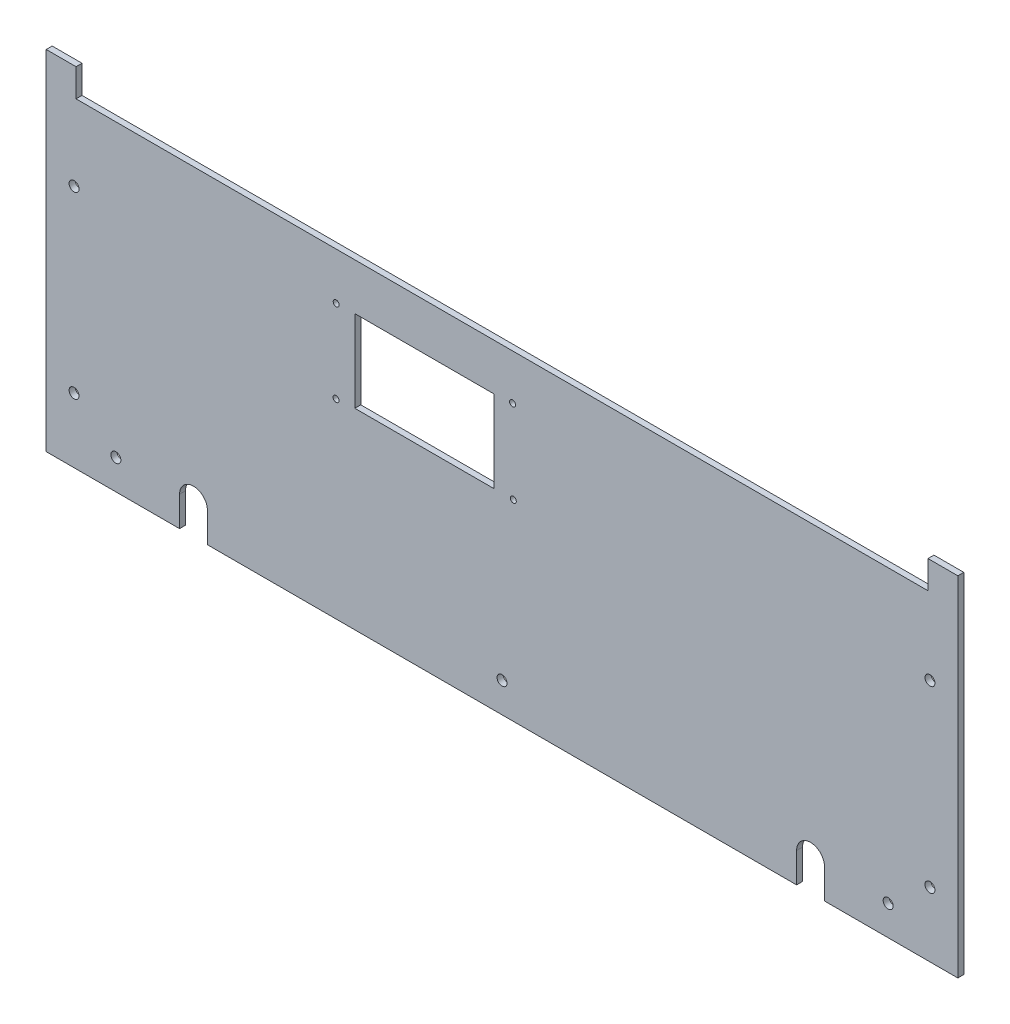
SolidWorks part; units mm, degrees
material "1345 Alloy"
ref_plane "Front Plane" through (0, 0, 0) normal (0, 0, 1) x (1, 0, 0)
ref_plane "Top Plane" through (0, 0, 0) normal (0, 1, 0) x (1, 0, 0)
ref_plane "Right Plane" through (0, 0, 0) normal (1, 0, 0) x (0, 0, -1)
sketch "Sketch1" plane through (0, 0, 0) normal (0, 0, 1) x (1, 0, 0)
  line L1 (-229, 122.5) -> (229, 122.5)
  line L2 (-229, 122.5) -> (-229, -122.5)
  line L3 (-229, -122.5) -> (229, -122.5)
  line L4 (229, 122.5) -> (229, -122.5)
  line L5 (-229, 122.5) -> (229, -122.5) construction
  line L6 (-229, -122.5) -> (229, 122.5) construction
  point P0 (0, 0)
  dimension "D1" = 458
  dimension "D2" = 245
extrude "Boss-Extrude1" add sketch "Sketch1" along normal blind 3
sketch "Sketch2" plane through (0, 0, 3) normal (0, 0, 1) x (1, 0, 0)
  line L0 (-229, -122.5) -> (-155, -122.5) construction
  line L2 (-155, -122.5) -> (-155, -107.5) construction
  line L3 (-155, -107.5) -> (-155, -122.5) construction
  line L6 (-148, -107.5) -> (-148, -122.5)
  line L11 (-162, -107.5) -> (-162, -122.5)
  line L12 (155, -122.5) -> (229, -122.5) construction
  line L13 (155, -107.5) -> (155, -122.5) construction
  line L14 (162, -107.5) -> (162, -122.5)
  line L15 (148, -107.5) -> (148, -122.5)
  line L16 (-155, -107.5) -> (155, -107.5) construction
  arc A4 (-148, -107.5) -> (-162, -107.5) centre (-155, -107.5) ccw
  arc A5 (-162, -122.5) -> (-148, -122.5) centre (-155, -122.5) ccw
  arc A6 (162, -107.5) -> (148, -107.5) centre (155, -107.5) ccw
  arc A7 (148, -122.5) -> (162, -122.5) centre (155, -122.5) ccw
  point P4 (-155, -115)
  point P13 (155, -115)
  dimension "D3" = 7
  dimension "D5" = 7
  dimension "D1" = 74
  dimension "D2" = 15
  dimension "D4" = 15
  dimension "D6" = 74
extrude "Cut-Extrude1" cut sketch "Sketch2" against normal through all
sketch "Sketch3" plane through (0, 0, 3) normal (0, 0, 1) x (1, 0, 0)
  line L19 (194, 112.5) -> (194, -107.5) construction
  line L20 (-215, 0) -> (-215, 90) construction
  line L21 (-215, 0) -> (-215, -90) construction
  line L25 (229, 0) -> (215, 0) construction
  line L26 (0, 112.5) -> (-194, 112.5) construction
  line L27 (-194, 112.5) -> (-194, -107.5) construction
  line L31 (215, 0) -> (215, 90) construction
  line L32 (215, 0) -> (215, -90) construction
  line L33 (0, 112.5) -> (194, 112.5) construction
  line L34 (0, 0) -> (0, 112.5) construction
  line L35 (0, 0) -> (0, -107.5) construction
  line L36 (-194, -107.5) -> (0, -107.5) construction
  line L37 (0, -107.5) -> (194, -107.5) construction
  line L38 (-194, 112.5) -> (-229, 112.5) construction
  line L39 (-229, 112.5) -> (-229, 122.5) construction
  circle A12 centre (-194, 112.5) radius 2.5
  circle A13 centre (-194, -107.5) radius 2.5
  circle A14 centre (194, -107.5) radius 2.5
  circle A15 centre (194, 112.5) radius 2.5
  circle A16 centre (-215, 0) radius 2.5
  circle A17 centre (-215, -90) radius 2.5
  circle A18 centre (-215, 90) radius 2.5
  circle A19 centre (215, 0) radius 2.5
  circle A20 centre (215, -90) radius 2.5
  circle A21 centre (215, 90) radius 2.5
  circle A22 centre (0, 112.5) radius 2.5
  circle A23 centre (0, -107.5) radius 2.5
  dimension "D3" = 5
  dimension "D6" = 90
  dimension "D9" = 5
  dimension "D12" = 90
  dimension "D15" = 5
  dimension "D16" = 194
  dimension "D17" = 194
  dimension "D2" = 5
  dimension "D4" = 5
  dimension "D5" = 5
  dimension "D8" = 5
  dimension "D10" = 5
  dimension "D14" = 5
  dimension "D7" = 90
  dimension "D11" = 14
  dimension "D13" = 90
  dimension "D18" = 194
  dimension "D19" = 194
extrude "Cut-Extrude2" cut sketch "Sketch3" against normal through all
sketch "Sketch4" plane through (0, 0, 3) normal (0, 0, 1) x (1, 0, 0)
  line L5 (0, 122.5) -> (0, 102.5) construction
  line L6 (229, 122.5) -> (-229, 122.5) construction
  line L7 (0, 102.5) -> (0, 82.5) construction
  line L8 (229, 91) -> (39, 91) construction
  line L10 (-39, 102.5) -> (-39, 122.5) construction
  line L11 (229, -122.5) -> (229, 122.5) construction
  line L12 (-229, 91) -> (-39, 91) construction
  line L13 (-229, 122.5) -> (-229, -122.5) construction
  line L14 (-39, 91) -> (0, 91) construction
  circle A1 centre (-39, 91) radius 11.5
  circle A2 centre (39, 91) radius 11.5
  dimension "D6" = 190
  dimension "D4" = 23
  dimension "D7" = 23
  dimension "D1" = 20
  dimension "D2" = 20
  dimension "D3" = 20
  dimension "D5" = 190
extrude "Cut-Extrude3" cut sketch "Sketch4" against normal through all
sketch "Sketch5" plane through (0, 0, 3) normal (0, 0, 1) x (1, 0, 0)
  line L0 (-229, -122) -> (-229, 53) construction
  line L1 (-229, 53) -> (229, 53) construction
  line L2 (-229, 53) -> (-229, 67.5) construction
  line L3 (-229, 67.5) -> (-214, 67.5) construction
  line L4 (229, 53) -> (229, 67.5) construction
  line L5 (229, 67.5) -> (214, 67.5) construction
  line L6 (214, 67.5) -> (-214, 67.5)
  line L7 (-214, 67.5) -> (-214, 38.5)
  line L8 (-214, 38.5) -> (214, 38.5)
  line L9 (214, 38.5) -> (214, 67.5)
  dimension "D1" = 175
  dimension "D2" = 14.5
  dimension "D3" = 15
  dimension "D4" = 14.5
  dimension "D5" = 15
  dimension "D6" = 29
extrude "Cut-Extrude4" cut sketch "Sketch5" against normal through all
sketch "Sketch8" plane through (0, 0, 3) normal (0, 0, 1) x (1, 0, 0)
  line L0 (-39, -5.5) -> (-39, 79.5) construction
  line L1 (-73.95, 15.1) -> (-4.05, 15.1)
  line L2 (-73.95, 15.1) -> (-73.95, -26.1)
  line L3 (-73.95, -26.1) -> (-4.05, -26.1)
  line L4 (-4.05, 15.1) -> (-4.05, -26.1)
  line L5 (-73.95, 15.1) -> (-4.05, -26.1) construction
  line L6 (-73.95, -26.1) -> (-4.05, 15.1) construction
  line L12 (5.6797, -26.0547) -> (-83.3, 14.88) construction
  line L13 (5.2962, 15.7036) -> (-83.368, -26.7379) construction
  circle A1 centre (-39, 91) radius 11.5 construction
  circle A2 centre (5.2962, 15.7036) radius 1.5
  circle A3 centre (5.6797, -26.0547) radius 1.5
  circle A4 centre (-83.3, 14.88) radius 1.5
  circle A5 centre (-83.368, -26.7379) radius 1.5
  point P0 (-39, -5.5)
  dimension "D6" = 3
  dimension "D7" = 3
  dimension "D8" = 3
  dimension "D9" = 3
  dimension "D1" = 69.9
  dimension "D2" = 41.2
  dimension "D3" = 85
  dimension "D4" = 88.6
  dimension "D5" = 41.76
extrude "Cut-Extrude5" cut sketch "Sketch8" against normal through all
sketch "Sketch9" plane through (0, 0, 3) normal (0, 0, 1) x (1, 0, 0)
  line L0 (-229, 122.5) -> (-229, 52.5) construction
  line L1 (-229, 122.5) -> (-229, -122.5) construction
  line L3 (-229, 52.5) -> (229, 52.5)
  line L4 (-229, 52.5) -> (-229, 122.5)
  line L5 (-229, 122.5) -> (229, 122.5)
  line L6 (229, 52.5) -> (229, 122.5)
  dimension "D1" = 70
extrude "Cut-Extrude6" cut sketch "Sketch9" against normal blind 10
